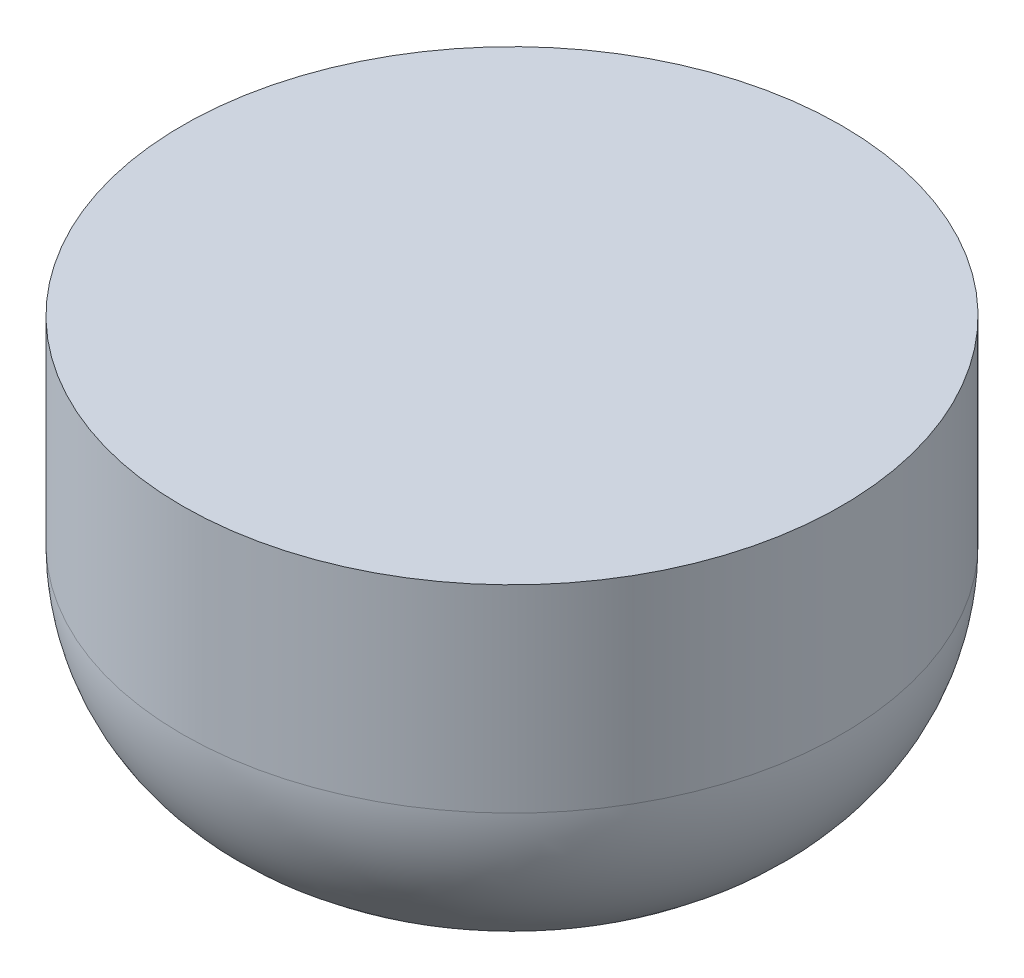
SolidWorks part; units mm, degrees
material "Rubber"
ref_plane "Front Plane" through (0, 0, 0) normal (0, 0, 1) x (1, 0, 0)
ref_plane "Top Plane" through (0, 0, 0) normal (0, 1, 0) x (1, 0, 0)
ref_plane "Right Plane" through (0, 0, 0) normal (1, 0, 0) x (0, 0, -1)
sketch "Sketch2" plane through (0, 0, 0) normal (0, 1, 0) x (1, 0, 0)
  circle A0 centre (0, 0) radius 2.5
  dimension "D1" = 5
extrude "Boss-Extrude1" add sketch "Sketch2" along normal blind 3
fillet "Fillet1" radius 1.5 1 edges at (0, 0, 2.5)
